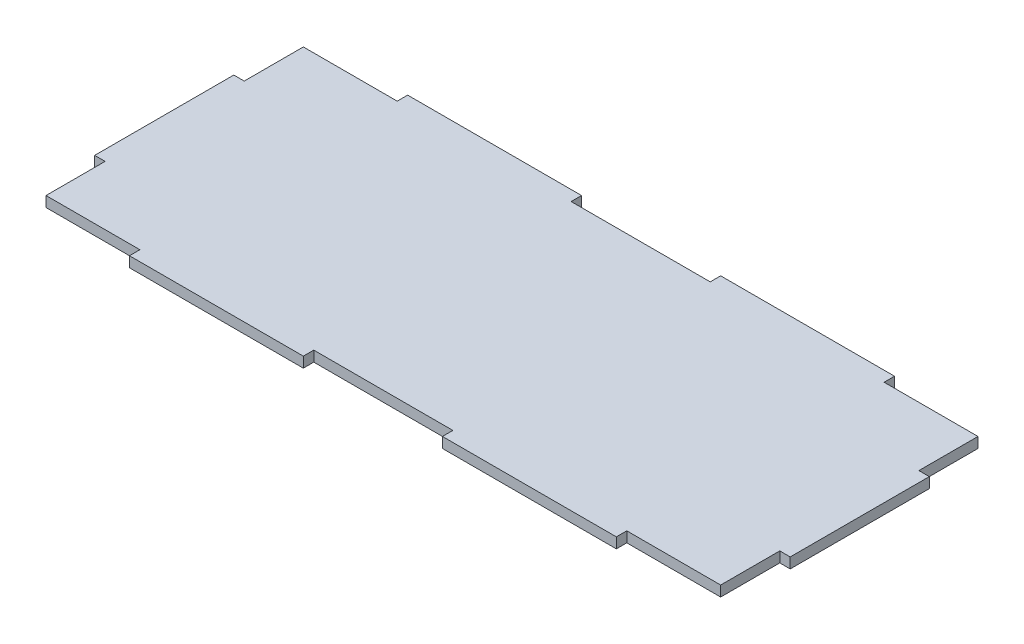
SolidWorks part; units mm, degrees
ref_plane "Plan de face" through (0, 0, 0) normal (0, 0, 1) x (1, 0, 0)
ref_plane "Plan de dessus" through (0, 0, 0) normal (0, 1, 0) x (1, 0, 0)
ref_plane "Plan de droite" through (0, 0, 0) normal (1, 0, 0) x (0, 0, -1)
sketch "Esquisse1" plane through (0, 0, 0) normal (0, 1, 0) x (1, 0, 0)
  line L0 (-36.0538, 28.5132) -> (13.9462, 28.5132)
  line L1 (53.9462, 28.5132) -> (103.9462, 28.5132)
  line L2 (-66.0538, 8.5132) -> (-66.0538, -31.4868)
  line L3 (-36.0538, -51.4868) -> (13.9462, -51.4868)
  line L4 (133.9462, 8.5132) -> (133.9462, -31.4868)
  line L5 (53.9462, -51.4868) -> (103.9462, -51.4868)
  line L7 (-63.0538, 25.5132) -> (-36.0538, 25.5132)
  line L8 (-36.0538, 28.5132) -> (-36.0538, 25.5132)
  line L10 (13.9462, 28.5132) -> (13.9462, 25.5132)
  line L11 (13.9462, 25.5132) -> (53.9462, 25.5132)
  line L12 (53.9462, 28.5132) -> (53.9462, 25.5132)
  line L15 (130.9462, 25.5132) -> (103.9462, 25.5132)
  line L16 (103.9462, 28.5132) -> (103.9462, 25.5132)
  line L19 (-66.0538, 8.5132) -> (-63.0538, 8.5132)
  line L20 (-63.0538, 25.5132) -> (-63.0538, 8.5132)
  line L23 (-66.0538, -31.4868) -> (-63.0538, -31.4868)
  line L24 (-63.0538, -48.4868) -> (-63.0538, -31.4868)
  line L27 (-63.0538, -48.4868) -> (-36.0538, -48.4868)
  line L28 (-36.0538, -51.4868) -> (-36.0538, -48.4868)
  line L30 (13.9462, -51.4868) -> (13.9462, -48.4868)
  line L31 (13.9462, -48.4868) -> (53.9462, -48.4868)
  line L32 (53.9462, -51.4868) -> (53.9462, -48.4868)
  line L35 (130.9462, -48.4868) -> (103.9462, -48.4868)
  line L36 (103.9462, -51.4868) -> (103.9462, -48.4868)
  line L39 (133.9462, -31.4868) -> (130.9462, -31.4868)
  line L40 (130.9462, -48.4868) -> (130.9462, -31.4868)
  line L43 (133.9462, 8.5132) -> (130.9462, 8.5132)
  line L44 (130.9462, 25.5132) -> (130.9462, 8.5132)
  dimension "D1" = 200
  dimension "D2" = 80
  dimension "D3" = 3
  dimension "D4" = 40
  dimension "D5" = 50
  dimension "D6" = 40
  dimension "D7" = 50
extrude "Boss.-Extru.1" add sketch "Esquisse1" along normal blind 3
